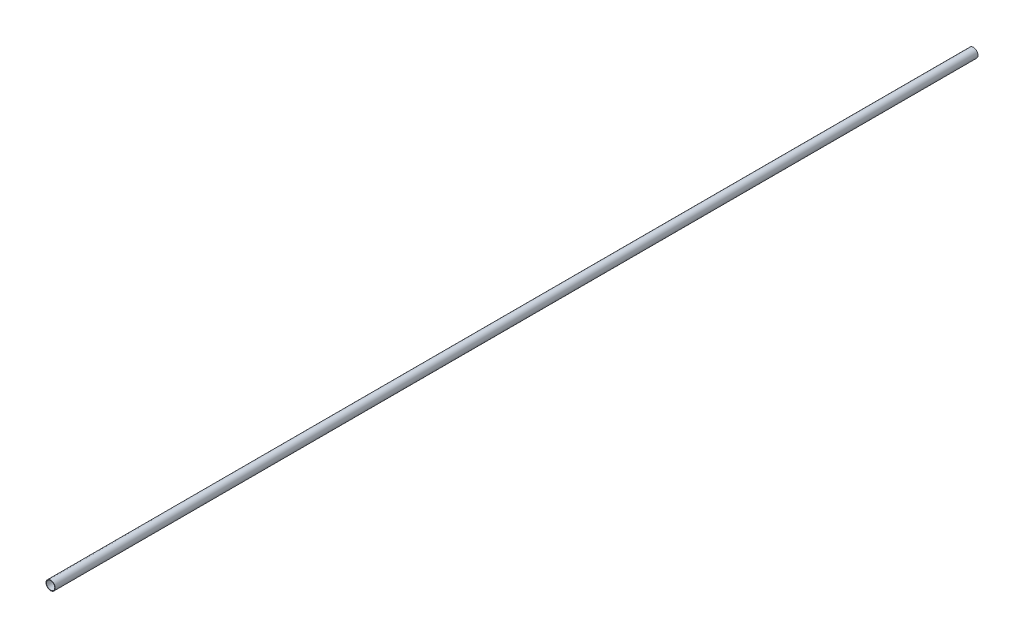
SolidWorks part; units mm, degrees
ref_plane "Front Plane" through (0, 0, 0) normal (0, 0, 1) x (1, 0, 0)
ref_plane "Top Plane" through (0, 0, 0) normal (0, 1, 0) x (1, 0, 0)
ref_plane "Right Plane" through (0, 0, 0) normal (1, 0, 0) x (0, 0, -1)
sketch "Sketch2" plane through (0, 0, 0) normal (0, 0, 1) x (1, 0, 0)
  circle A0 centre (0, 0) radius 5
  dimension "D1" = 10
extrude "Boss-Extrude1" add sketch "Sketch2" along normal blind 1000
sketch "Sketch3" plane through (0, 0, 1000) normal (0, 0, 1) x (1, 0, 0)
  circle A0 centre (0, 0) radius 4.5
  dimension "D1" = 9
extrude "Cut-Extrude1" cut sketch "Sketch3" against normal through all
